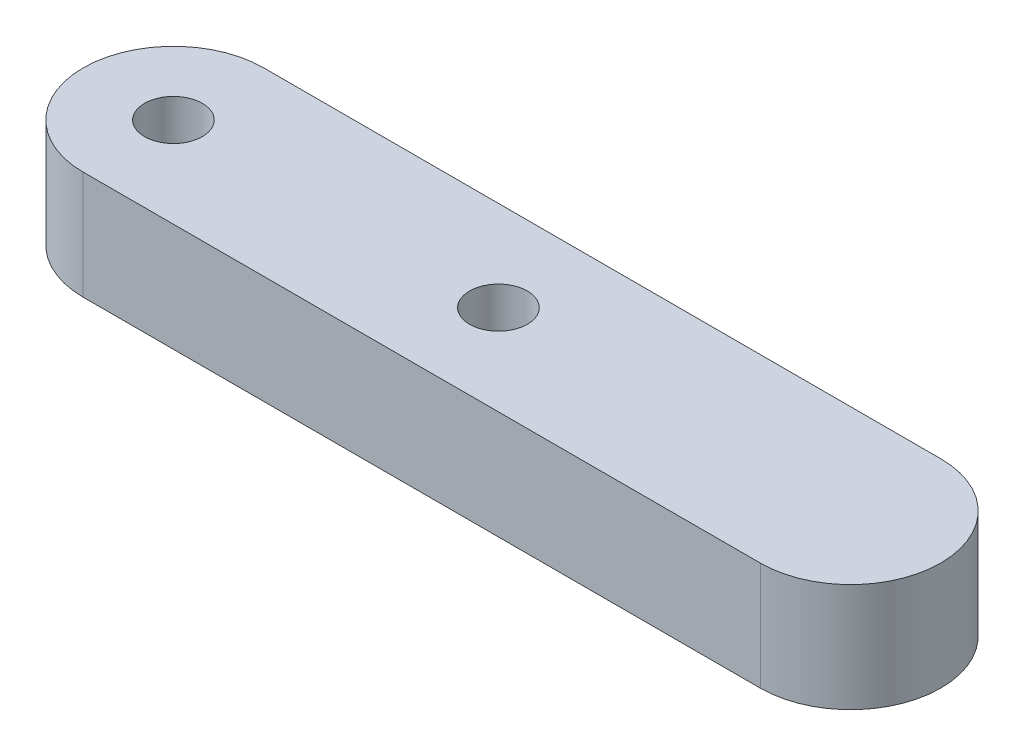
SolidWorks part; units mm, degrees
material "Acrylic (Medium-high impact)"
ref_plane "Front Plane" through (0, 0, 0) normal (0, 0, 1) x (1, 0, 0)
ref_plane "Top Plane" through (0, 0, 0) normal (0, 1, 0) x (1, 0, 0)
ref_plane "Right Plane" through (0, 0, 0) normal (1, 0, 0) x (0, 0, -1)
sketch "Sketch1" plane through (0, 0, 0) normal (0, 1, 0) x (1, 0, 0)
  line L0 (-18.75, 0) -> (18.75, 0) construction
  line L1 (-18.75, 5) -> (18.75, 5)
  line L2 (-18.75, -5) -> (18.75, -5)
  arc A0 (-18.75, 5) -> (-18.75, -5) centre (-18.75, 0) ccw
  arc A1 (18.75, -5) -> (18.75, 5) centre (18.75, 0) ccw
  circle A2 centre (-18.75, 0) radius 1.6
  circle A3 centre (-0.75, 0) radius 1.6
  point P2 (0, 0)
  dimension "D3" = 3.2
  dimension "D4" = 3.2
  dimension "D1" = 10
  dimension "D2" = 37.5
  dimension "D5" = 18
extrude "Boss-Extrude1" add sketch "Sketch1" along normal blind 6
